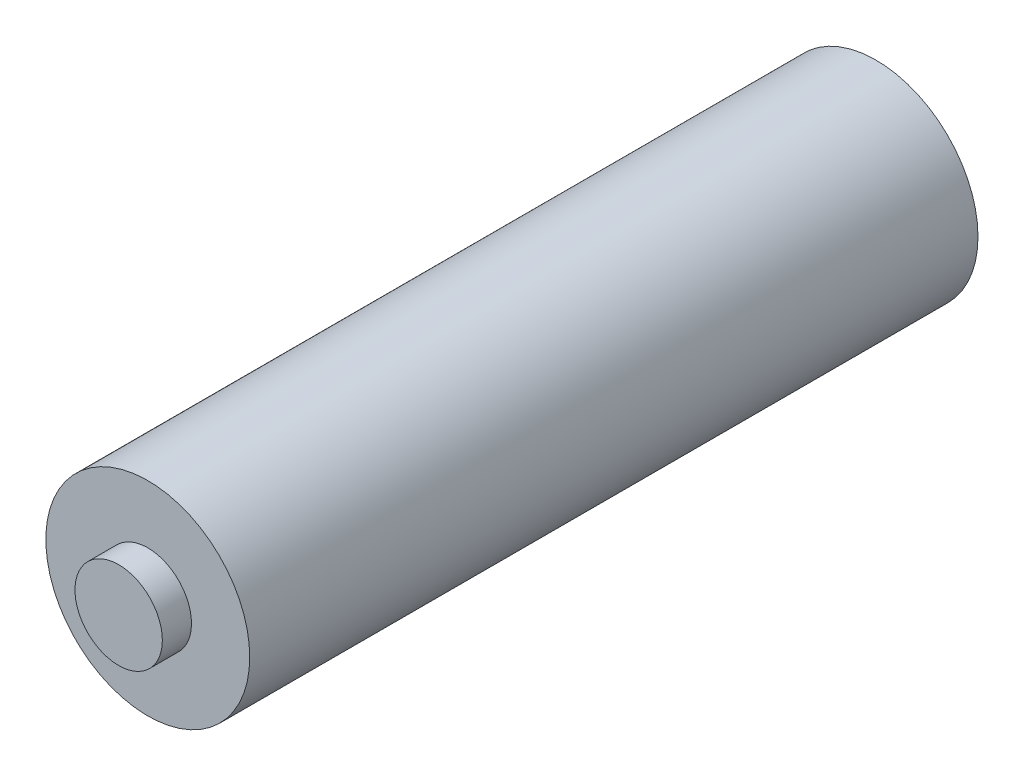
SolidWorks part; units mm, degrees
ref_plane "Front Plane" through (0, 0, 0) normal (0, 0, 1) x (1, 0, 0)
ref_plane "Top Plane" through (0, 0, 0) normal (0, 1, 0) x (1, 0, 0)
ref_plane "Right Plane" through (0, 0, 0) normal (1, 0, 0) x (0, 0, -1)
sketch "Sketch1" plane through (0, 0, 0) normal (0, 0, 1) x (1, 0, 0)
  circle A0 centre (0, 0) radius 17.5
  dimension "D1" = 35
extrude "Boss-Extrude1" add sketch "Sketch1" along normal blind 125
sketch "Sketch2" plane through (0, 0, 125) normal (0, 0, 1) x (1, 0, 0)
  circle A0 centre (0, 0) radius 7.5
  dimension "D1" = 15
extrude "Boss-Extrude2" add sketch "Sketch2" along normal blind 5
sketch "Sketch3" plane through (0, 0, 0) normal (0, 0, -1) x (-1, 0, 0)
  circle A0 centre (0, 0) radius 7.5
  dimension "D1" = 15
extrude "Boss-Extrude3" add sketch "Sketch3" along normal blind 5
